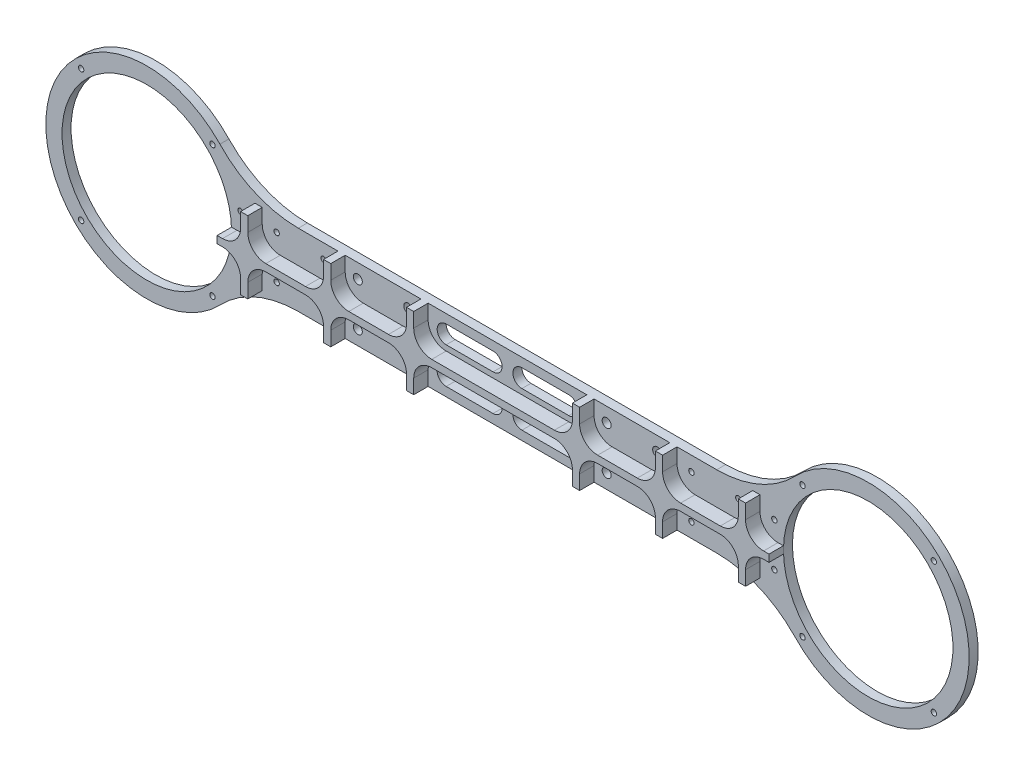
SolidWorks part; units mm, degrees
material "7075-T6，板材(SS)"
ref_plane "前视基准面" through (0, 0, 0) normal (0, 0, 1) x (1, 0, 0)
ref_plane "上视基准面" through (0, 0, 0) normal (0, 1, 0) x (1, 0, 0)
ref_plane "右视基准面" through (0, 0, 0) normal (1, 0, 0) x (0, 0, -1)
sketch "草图1" plane through (0, 0, 0) normal (0, 0, 1) x (1, 0, 0)
  line L0 (0, 0) -> (400, 0) construction
  line L3 (347.6932, 20) -> (52.3068, 20)
  line L5 (347.6932, -20) -> (52.3068, -20)
  circle A0 centre (0, 0) radius 47
  arc A1 (52.3068, 20) -> (52.3068, -20) centre (0, 0) ccw
  circle A2 centre (400, 0) radius 47
  arc A3 (347.6932, -20) -> (347.6932, 20) centre (400, 0) ccw
  dimension "D1" = 56
  dimension "D2" = 56
  dimension "D3" = 400
  dimension "D4" = 40
  dimension "D5" = 20
extrude "凸台-拉伸1" add sketch "草图1" along normal blind 5
fillet "圆角1" radius 60 4 edges at (52.3068, 20, 2.5) (52.3068, -20, 2.5) (347.6932, -20, 2.5) (347.6932, 20, 2.5)
sketch "草图31" plane through (0, 0, 5) normal (0, 0, 1) x (1, 0, 0)
  line L0 (0, 0) -> (36.416, 36.416) construction
  line L1 (200, 20) -> (200, -66.2519) construction
  line L2 (316, 20) -> (84, 20) construction
  line L3 (400, 0) -> (363.584, 36.416) construction
  circle A0 centre (0, 0) radius 51.5 construction
  circle A1 centre (36.416, 36.416) radius 1.5
  circle A2 centre (36.416, -36.416) radius 1.5
  circle A3 centre (-36.416, -36.416) radius 1.5
  circle A4 centre (-36.416, 36.416) radius 1.5
  circle A5 centre (400, 0) radius 51.5 construction
  circle A6 centre (436.416, 36.416) radius 1.5
  circle A7 centre (436.416, -36.416) radius 1.5
  circle A8 centre (363.584, -36.416) radius 1.5
  circle A9 centre (363.584, 36.416) radius 1.5
  point P14 (0, 0)
  point P26 (500, 0)
  dimension "D1" = 4
extrude "切除-拉伸14" cut sketch "草图31" against normal blind 5
sketch "草图32" plane through (0, 0, 5) normal (0, 0, 1) x (1, 0, 0)
  line L0 (200, 20) -> (200, -20) construction
  line L1 (316, 20) -> (84, 20) construction
  line L2 (84, -20) -> (316, -20) construction
  line L4 (47, 2) -> (353, 2)
  line L5 (47, 2) -> (47, -2)
  line L6 (47, -2) -> (353, -2)
  line L7 (353, 2) -> (353, -2)
  line L8 (47, 2) -> (353, -2) construction
  line L9 (47, -2) -> (353, 2) construction
  point P6 (200, 0)
  dimension "D1" = 4
  dimension "D2" = 306
extrude "凸台-拉伸2" add sketch "草图32" along normal blind 8
sketch "草图34" plane through (0, 0, 5) normal (0, 0, 1) x (1, 0, 0)
  line L0 (200, 20) -> (200, -20) construction
  line L1 (316, 20) -> (84, 20) construction
  line L2 (84, -20) -> (316, -20) construction
  line L3 (200, -20) -> (200, -10) construction
  line L4 (200, -10) -> (200, 10) construction
  line L6 (164, 5) -> (192, 5)
  line L8 (164, 15) -> (192, 15)
  line L10 (197, 10) -> (192, 10) construction
  line L11 (164, -15) -> (192, -15)
  line L12 (164, -5) -> (192, -5)
  line L17 (203, 10) -> (208, 10) construction
  line L19 (200, 0) -> (226.2289, 0) construction
  line L20 (208, 15) -> (236, 15)
  line L25 (108, 20) -> (108, -15) construction
  line L26 (108, -15) -> (108, -10) construction
  line L27 (108, -10) -> (108, 10) construction
  line L28 (-45, 0) -> (47, 0) construction
  line L29 (208, 5) -> (236, 5)
  line L32 (208, -5) -> (236, -5)
  line L33 (208, -15) -> (236, -15)
  line L38 (292, 5) -> (292, 10) construction
  line L42 (292, 10) -> (292, 5) construction
  line L45 (72, 15) -> (100, 15) [skipped]
  line L46 (72, 5) -> (100, 5) [skipped]
  line L47 (72, -5) -> (100, -5) [skipped]
  line L48 (72, -15) -> (100, -15) [skipped]
  arc A0 (164, 15) -> (164, 5) centre (164, 10) ccw
  arc A1 (236, 5) -> (236, 15) centre (236, 10) ccw
  arc A2 (236, -5) -> (236, -15) centre (236, -10) cw
  arc A3 (164, -15) -> (164, -5) centre (164, -10) cw
  arc A20 (72, -15) -> (72, -5) centre (72, -10) cw [skipped]
  arc A21 (72, 15) -> (72, 5) centre (72, 10) ccw [skipped]
  arc A22 (192, 5) -> (192, 15) centre (192, 10) ccw
  arc A23 (208, 15) -> (208, 5) centre (208, 10) ccw
  arc A24 (144, 5) -> (144, 15) centre (144, 10) ccw [skipped]
  arc A25 (144, -5) -> (144, -15) centre (144, -10) cw [skipped]
  arc A26 (208, -15) -> (208, -5) centre (208, -10) cw
  arc A27 (192, -5) -> (192, -15) centre (192, -10) cw
  dimension "D5" = 8
  dimension "D7" = 8
  dimension "D1" = 10
  dimension "D2" = 20
  dimension "D3" = 10
  dimension "D4" = 72
  dimension "D6" = 2
extrude "切除-拉伸17" cut sketch "草图34" against normal blind 8
sketch "草图35" plane through (0, 0, 5) normal (0, 0, 1) x (1, 0, 0)
  line L0 (200, 20) -> (200, -20) construction
  line L2 (316, 20) -> (84, 20) construction
  line L7 (84, -20) -> (316, -20) construction
  line L9 (145, -12) -> (255, -12) construction
  line L10 (145, -12) -> (145, 12) construction
  line L11 (145, 12) -> (255, 12) construction
  line L12 (255, -12) -> (255, 12) construction
  line L13 (145, -12) -> (255, 12) construction
  line L14 (145, 12) -> (255, -12) construction
  circle A4 centre (145, 12) radius 2.5
  circle A5 centre (145, -12) radius 2.5
  circle A6 centre (255, 12) radius 2.5
  circle A7 centre (255, -12) radius 2.5
  point P6 (200, 0)
  dimension "D3" = 5
  dimension "D4" = 5
  dimension "D5" = 5
  dimension "D6" = 5
  dimension "D1" = 24
  dimension "D2" = 110
extrude "切除-拉伸18" cut sketch "草图35" against normal blind 10
sketch "草图36" plane through (0, 0, 5) normal (0, 0, 1) x (1, 0, 0)
  line L0 (164, 15) -> (166, 15)
  line L1 (164, 5) -> (166, 5)
  line L2 (164, -5) -> (166, -5)
  line L3 (164, -15) -> (166, -15)
  line L4 (234, 15) -> (236, 15)
  line L5 (234, 5) -> (236, 5)
  line L6 (234, -5) -> (236, -5)
  line L7 (234, -15) -> (236, -15)
  arc A0 (236, -15) -> (236, -5) centre (236, -10) ccw construction
  arc A1 (236, 5) -> (236, 15) centre (236, 10) ccw construction
  arc A2 (164, -5) -> (164, -15) centre (164, -10) ccw construction
  arc A3 (164, 15) -> (164, 5) centre (164, 10) ccw construction
  arc A4 (236, -15) -> (236, -5) centre (236, -10) ccw
  arc A5 (236, 5) -> (236, 15) centre (236, 10) ccw
  arc A6 (164, -5) -> (164, -15) centre (164, -10) ccw
  arc A7 (164, 15) -> (164, 5) centre (164, 10) ccw
  arc A8 (166, -5) -> (166, -15) centre (166, -10) ccw
  arc A9 (166, 15) -> (166, 5) centre (166, 10) ccw
  arc A10 (234, -15) -> (234, -5) centre (234, -10) ccw
  arc A11 (234, 5) -> (234, 15) centre (234, 10) ccw
  dimension "D1" = 2
  dimension "D2" = 2
extrude "凸台-拉伸3" add sketch "草图36" against normal up to surface (5 mm away) up to face at (147.5, -12, 0)
sketch "草图37" plane through (0, 0, 5) normal (0, 0, 1) x (1, 0, 0)
  line L0 (200, 20) -> (200, -20) construction
  line L1 (316, 20) -> (84, 20) construction
  line L2 (84, -20) -> (316, -20) construction
  line L3 (52, 12) -> (52, -12) construction
  line L4 (52, -12) -> (72.002, -12) construction
  line L5 (72.002, -12) -> (72.002, 12) construction
  line L6 (327.998, 12) -> (327.998, -12) construction
  line L7 (348, 12) -> (348, -12) construction
  circle A4 centre (72.002, -12) radius 1.5
  circle A5 centre (72.002, 12) radius 1.5
  circle A6 centre (52, -12) radius 1.5
  circle A7 centre (52, 12) radius 1.5
  circle A8 centre (348, 12) radius 1.5
  circle A9 centre (348, -12) radius 1.5
  circle A10 centre (327.998, 12) radius 1.5
  circle A11 centre (327.998, -12) radius 1.5
extrude "切除-拉伸19" cut sketch "草图37" against normal blind 10
sketch "草图38" plane through (0, 0, 5) normal (0, 0, 1) x (1, 0, 0)
  line L0 (52, 12) -> (52, -12) construction
  line L1 (72.002, 12) -> (72.002, -12) construction
  line L2 (52, 0) -> (72.002, 0) construction
  line L3 (62.001, 0) -> (108.001, 0) construction
  line L4 (60.001, -20) -> (64.001, -20)
  line L5 (60.001, -20) -> (60.001, 20)
  line L6 (60.001, 20) -> (64.001, 20)
  line L7 (64.001, -20) -> (64.001, 20)
  line L8 (60.001, -20) -> (64.001, 20) construction
  line L9 (60.001, 20) -> (64.001, -20) construction
  line L10 (108.001, 0) -> (154.001, 0) construction
  line L12 (106.001, -20) -> (110.001, -20)
  line L13 (106.001, -20) -> (106.001, 20)
  line L14 (106.001, 20) -> (110.001, 20)
  line L15 (110.001, -20) -> (110.001, 20)
  line L16 (106.001, -20) -> (110.001, 20) construction
  line L17 (106.001, 20) -> (110.001, -20) construction
  line L18 (316, 20) -> (84, 20) construction
  line L19 (200, 20) -> (200, -20) construction
  line L20 (152.001, -20) -> (156.001, -20)
  line L21 (152.001, -20) -> (152.001, 20)
  line L22 (152.001, 20) -> (156.001, 20)
  line L23 (156.001, -20) -> (156.001, 20)
  line L24 (152.001, -20) -> (156.001, 20) construction
  line L25 (152.001, 20) -> (156.001, -20) construction
  line L26 (84, -20) -> (316, -20) construction
  line L27 (247.999, 20) -> (243.999, -20) construction
  line L28 (247.999, -20) -> (243.999, 20) construction
  line L29 (293.999, 20) -> (289.999, -20) construction
  line L30 (293.999, -20) -> (289.999, 20) construction
  line L31 (291.999, 0) -> (245.999, 0) construction
  line L32 (339.999, 20) -> (335.999, -20) construction
  line L33 (339.999, -20) -> (335.999, 20) construction
  line L34 (337.999, 0) -> (291.999, 0) construction
  line L35 (348, 0) -> (327.998, 0) construction
  line L36 (327.998, 12) -> (327.998, -12) construction
  line L37 (348, 12) -> (348, -12) construction
  line L38 (243.999, -20) -> (243.999, 20)
  line L39 (247.999, 20) -> (243.999, 20)
  line L40 (247.999, -20) -> (247.999, 20)
  line L41 (247.999, -20) -> (243.999, -20)
  line L42 (289.999, -20) -> (289.999, 20)
  line L43 (293.999, 20) -> (289.999, 20)
  line L44 (293.999, -20) -> (293.999, 20)
  line L45 (293.999, -20) -> (289.999, -20)
  line L46 (335.999, -20) -> (335.999, 20)
  line L47 (339.999, 20) -> (335.999, 20)
  line L48 (339.999, -20) -> (339.999, 20)
  line L49 (339.999, -20) -> (335.999, -20)
  point P10 (62.001, 0)
  dimension "D1" = 40
  dimension "D2" = 4
  dimension "D3" = 46
  dimension "D4" = 46
  dimension "D5" = 40
  dimension "D6" = 4
  dimension "D7" = 40
  dimension "D8" = 4
extrude "凸台-拉伸4" add sketch "草图38" along normal blind 8
fillet "圆角2" radius 10 24 edges at (335.999, -2, 9) (339.999, -2, 9) (339.999, 2, 9) (335.999, 2, 9) (293.999, 2, 9) (293.999, -2, 9) (289.999, -2, 9) (289.999, 2, 9) (247.999, 2, 9) (247.999, -2, 9) (243.999, -2, 9) (243.999, 2, 9) (156.001, 2, 9) (156.001, -2, 9) (152.001, -2, 9) (152.001, 2, 9) (64.001, -2, 9) (60.001, -2, 9) (106.001, -2, 9) (106.001, 2, 9) (64.001, 2, 9) (60.001, 2, 9) (110.001, -2, 9) (110.001, 2, 9)
sketch "草图41" plane through (0, 0, 5) normal (0, 0, 1) x (1, 0, 0)
  line L0 (85.001, 2) -> (85.001, 22.9084) construction
  line L1 (96.001, 2) -> (74.001, 2) construction
  line L2 (131.001, 2) -> (131.001, 26.695) construction
  line L3 (142.001, 2) -> (120.001, 2) construction
  line L4 (268.999, 2) -> (268.999, 30.9307) construction
  line L5 (279.999, 2) -> (257.999, 2) construction
  line L6 (314.999, 2) -> (314.999, 30.9307) construction
  line L7 (325.999, 2) -> (303.999, 2) construction
  circle A0 centre (327.998, -12) radius 1.5 construction
  circle A1 centre (327.998, 12) radius 1.5 construction
  circle A2 centre (255, -12) radius 2.5 construction
  circle A3 centre (255, 12) radius 2.5 construction
  circle A4 centre (145, -12) radius 2.5 construction
  circle A5 centre (145, 12) radius 2.5 construction
  circle A6 centre (72.002, -12) radius 1.5 construction
  circle A7 centre (72.002, 12) radius 1.5 construction
  circle A8 centre (327.998, -12) radius 1.5
  circle A9 centre (327.998, 12) radius 1.5
  circle A10 centre (255, -12) radius 2.5
  circle A11 centre (255, 12) radius 2.5
  circle A12 centre (145, -12) radius 2.5
  circle A13 centre (145, 12) radius 2.5
  circle A14 centre (72.002, -12) radius 1.5
  circle A15 centre (72.002, 12) radius 1.5
  circle A16 centre (98, -12) radius 1.5
  circle A17 centre (98, 12) radius 1.5
  circle A18 centre (117.002, -12) radius 2.5
  circle A19 centre (117.002, 12) radius 2.5
  circle A20 centre (282.998, -12) radius 2.5
  circle A21 centre (282.998, 12) radius 2.5
  circle A22 centre (302, -12) radius 1.5
  circle A23 centre (302, 12) radius 1.5
extrude "切除-拉伸20" cut sketch "草图41" against normal blind 10
equation "\"www\"=252"
